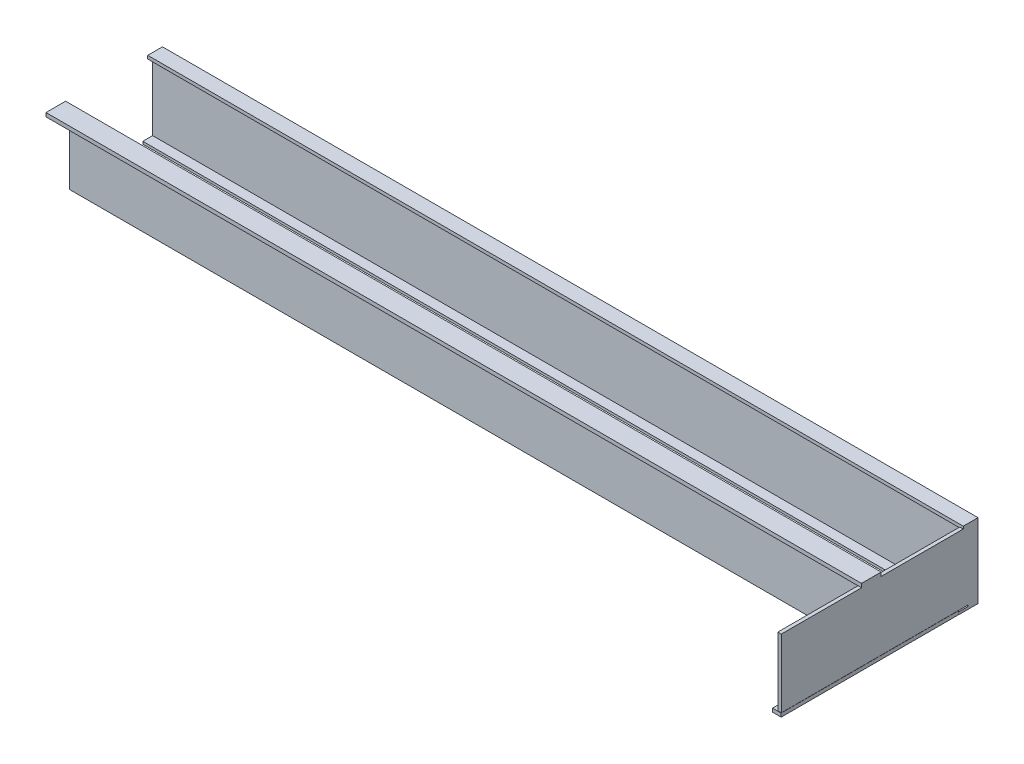
SolidWorks part; units mm, degrees
ref_plane "前视基准面" through (0, 0, 0) normal (0, 0, 1) x (1, 0, 0)
ref_plane "上视基准面" through (0, 0, 0) normal (0, 1, 0) x (1, 0, 0)
ref_plane "右视基准面" through (0, 0, 0) normal (1, 0, 0) x (0, 0, -1)
sketch "草图1" plane through (0, 0, 0) normal (0, 0, 1) x (1, 0, 0)
  line L1 (-77.3458, -35.3581) -> (752.6542, -35.3581)
  line L2 (-77.3458, -35.3581) -> (-77.3458, 47.5519)
  line L3 (-77.3458, 47.5519) -> (752.6542, 47.5519)
  line L4 (752.6542, -35.3581) -> (752.6542, 47.5519)
extrude "凸台-拉伸2" add sketch "草图1" along normal blind 20
ref_plane "基准面1" through (-77.3458, -35.3581, 20) normal (1, 0, 0) x (0, 0, -1)
sketch "草图4" plane through (0, 47.5519, 0) normal (0, 1, 0) x (1, 0, 0)
  line L0 (752.6542, -20) -> (752.6542, 0) construction
  line L1 (-77.3458, -20) -> (752.6542, -20)
  line L2 (-77.3458, -20) -> (-77.3458, -10)
  line L3 (-77.3458, -10) -> (752.6542, -10)
  line L4 (752.6542, -20) -> (752.6542, -10)
extrude "切除-拉伸3" cut sketch "草图4" against normal blind 70
sketch "草图5" plane through (0, 47.5519, 0) normal (0, 1, 0) x (1, 0, 0)
  line L0 (-77.3458, -248.25) -> (-77.3458, 208.25) construction
  line L1 (-77.3458, 0) -> (752.6542, 0)
  line L2 (-77.3458, 0) -> (-77.3458, -15)
  line L3 (-77.3458, -15) -> (752.6542, -15)
  line L4 (752.6542, 0) -> (752.6542, -15)
  line L5 (752.6542, -20) -> (752.6542, -10) construction
extrude "凸台-拉伸3" add sketch "草图5" along normal blind 3.28
ref_plane "基准面2" through (752.6542, 50.8319, 0) normal (0, 0, -1) x (-1, 0, 0)
sketch "草图6" plane through (752.6542, 50.8319, 0) normal (0, 0, -1) x (-1, 0, 0)
  line L0 (0, -86.19) -> (0, 0) construction
  line L1 (0, -2.5152) -> (3.54, -2.5152)
  line L2 (0, -2.5152) -> (0, -71.9152)
  line L3 (0, -71.9152) -> (3.54, -71.9152)
  line L4 (3.54, -2.5152) -> (3.54, -71.9152)
extrude "凸台-拉伸5" add sketch "草图6" against normal blind 200.2
ref_plane "基准面3" through (749.1142, -21.0833, 200.2) normal (0, 0, -1) x (-1, 0, 0)
sketch "草图8" plane through (-77.3458, 0, 0) normal (-1, 0, 0) x (0, 0, 1)
  line L0 (20, -22.4481) -> (20, -35.3581) construction
  line L1 (0, -35.3581) -> (20, -35.3581)
  line L2 (0, -35.3581) -> (0, -24.9583)
  line L3 (0, -24.9583) -> (20, -24.9583)
  line L4 (20, -35.3581) -> (20, -24.9583)
extrude "切除-拉伸5" cut sketch "草图8" against normal blind 1000.2
sketch "草图9" plane through (0, -21.0833, 0) normal (0, -1, 0) x (1, 0, 0)
  line L1 (752.821, 19.7778) -> (744.0902, 19.7778)
  line L2 (752.821, 19.7778) -> (752.821, 200.53)
  line L3 (752.821, 200.53) -> (744.0902, 200.53)
  line L4 (744.0902, 19.7778) -> (744.0902, 200.53)
extrude "凸台-拉伸6" add sketch "草图9" along normal blind 3.62
sketch "草图10" plane through (749.1142, 0, 0) normal (-1, 0, 0) x (0, 0, 1)
  line L0 (200.2, 48.3167) -> (15, 48.3167) construction
  line L1 (98.0715, 48.3167) -> (101.1615, 48.3167)
  line L2 (98.0715, 48.3167) -> (98.0715, -21.0833)
  line L3 (98.0715, -21.0833) -> (101.1615, -21.0833)
  line L4 (101.1615, 48.3167) -> (101.1615, -21.0833)
  line L5 (200.2, -21.0833) -> (19.7778, -21.0833) construction
extrude "凸台-拉伸7" add sketch "草图10" along normal blind 820
ref_plane "基准面4" through (744.0902, -21.0833, 98.0715) normal (1, 0, 0) x (0, 0, -1)
ref_plane "基准面5" through (749.1142, 48.3167, 101.1615) normal (1, 0, 0) x (0, 0, -1)
sketch "草图13" plane through (0, 48.3167, 0) normal (0, 1, 0) x (1, 0, 0)
  line L0 (752.6542, -200.2) -> (752.6542, -19.7778) construction
  line L1 (752.6542, -98.539) -> (-77.3458, -98.539)
  line L2 (752.6542, -98.539) -> (752.6542, -118.539)
  line L3 (752.6542, -118.539) -> (-77.3458, -118.539)
  line L4 (-77.3458, -98.539) -> (-77.3458, -118.539)
  line L5 (-77.3458, -75) -> (-77.3458, 35) construction
extrude "凸台-拉伸18" add sketch "草图13" along normal blind 3.85
